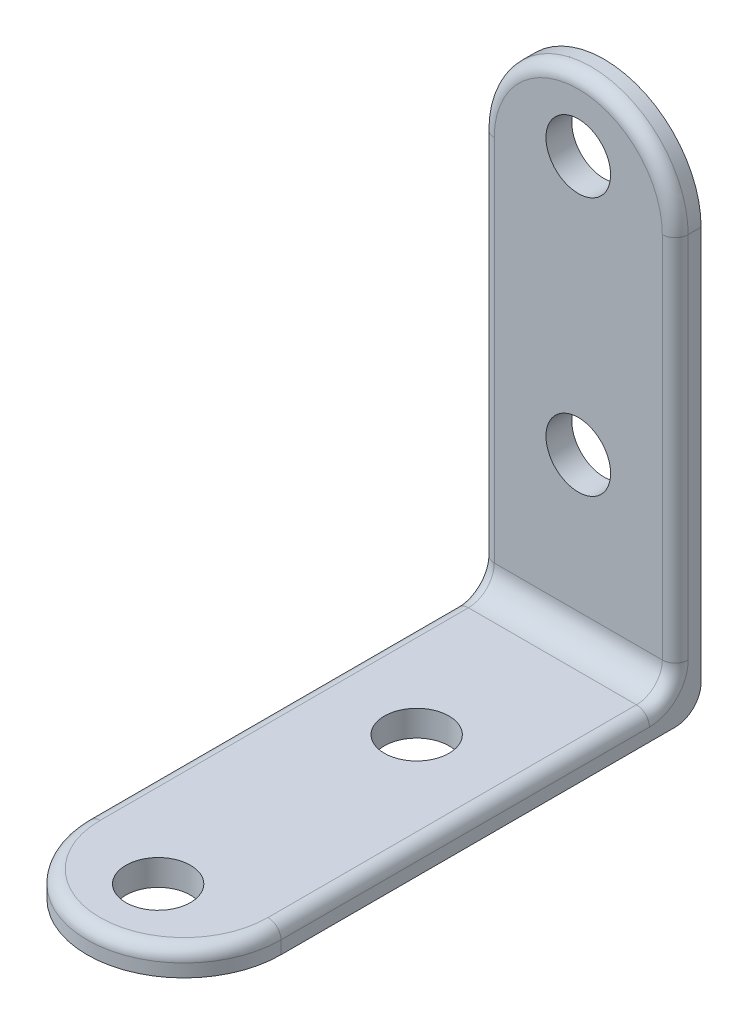
SolidWorks part; units mm, degrees
ref_plane "Front Plane" through (0, 0, 0) normal (0, 0, 1) x (1, 0, 0)
ref_plane "Top Plane" through (0, 0, 0) normal (0, 1, 0) x (1, 0, 0)
ref_plane "Right Plane" through (0, 0, 0) normal (1, 0, 0) x (0, 0, -1)
sketch "Esquisse1" plane through (0, 0, 0) normal (0, 1, 0) x (1, 0, 0)
  line L0 (0, 0) -> (0, 24.2045) construction
  line L1 (-7.5, 0) -> (-7.5, 32.5)
  line L2 (7.5, 0) -> (7.5, 32.5)
  line L3 (-7.5, 32.5) -> (7.5, 32.5)
  line L4 (-6.8155, -7.5) -> (8.2512, -7.5)
  line L5 (0, 32.5) -> (0, 18) construction
  line L6 (0, 15.5) -> (0, -2) construction
  arc A0 (-7.5, 0) -> (7.5, 0) centre (0, 0) ccw
  circle A2 centre (0, 18) radius 2.5
  circle A3 centre (0, -2) radius 2.5
  point P3 (0, 12.1023)
  dimension "D2" = 40
  dimension "D4" = 5
  dimension "D5" = 17.5
  dimension "D6" = 5
  dimension "D1" = 15
  dimension "D3" = 14.5
extrude "Boss.-Extru.2" add sketch "Esquisse1" along normal blind 2 contours A0 L2 L3 L1 A3 A2
sketch "Esquisse2" plane through (0, 0, -32.5) normal (0, 0, -1) x (-1, 0, 0)
  line L1 (-7.5, 0) -> (-7.5, 32.5)
  line L2 (7.5, 0) -> (7.5, 32.5)
  line L3 (0, 0) -> (0, 22.2646) construction
  line L4 (-6.3055, 40) -> (7.5, 40)
  line L5 (-7.5, 0) -> (7.5, 0)
  line L6 (0, 17) -> (0, 34.9452) construction
  line L7 (0, 17) -> (0, 34.5) construction
  arc A1 (7.5, 32.5) -> (-7.5, 32.5) centre (0, 32.5) ccw
  circle A2 centre (0, 14.5) radius 2.5
  circle A3 centre (0, 34.5) radius 2.5
  point P3 (0, 14.5)
  point P10 (0, 40)
  line M6 (-7.5, 0) -> (7.5, 0)
  line M7 (7.5, 0) -> (7.5, 2)
  line M8 (7.5, 2) -> (-7.5, 2)
  line M9 (-7.5, 2) -> (-7.5, 0)
  dimension "D1" = 7.5
  dimension "D5" = 5
  dimension "D7" = 5
  dimension "D2" = 15
  dimension "D3" = 40
  dimension "D4" = 14.5
  dimension "D6" = 17.5
extrude "Boss.-Extru.3" add sketch "Esquisse2" against normal blind 2 contours L2 A1 L1 A3 A2 M8 | M9 M6 M7 M8
fillet "Congé1" radius 2 1 edges at (0, 0, -32.5)
fillet "Congé2" radius 2 1 edges at (0, 2, -30.5)
fillet "Congé4" radius 1 8 edges at (-7.5, 2, -14.25) (-7.5, 2.5858, -29.9142) (-7.5, 18.25, -30.5) (0, 40, -30.5) (7.5, 18.25, -30.5) (7.5, 2.5858, -29.9142) (7.5, 2, -14.25) (0, 2, 7.5)
